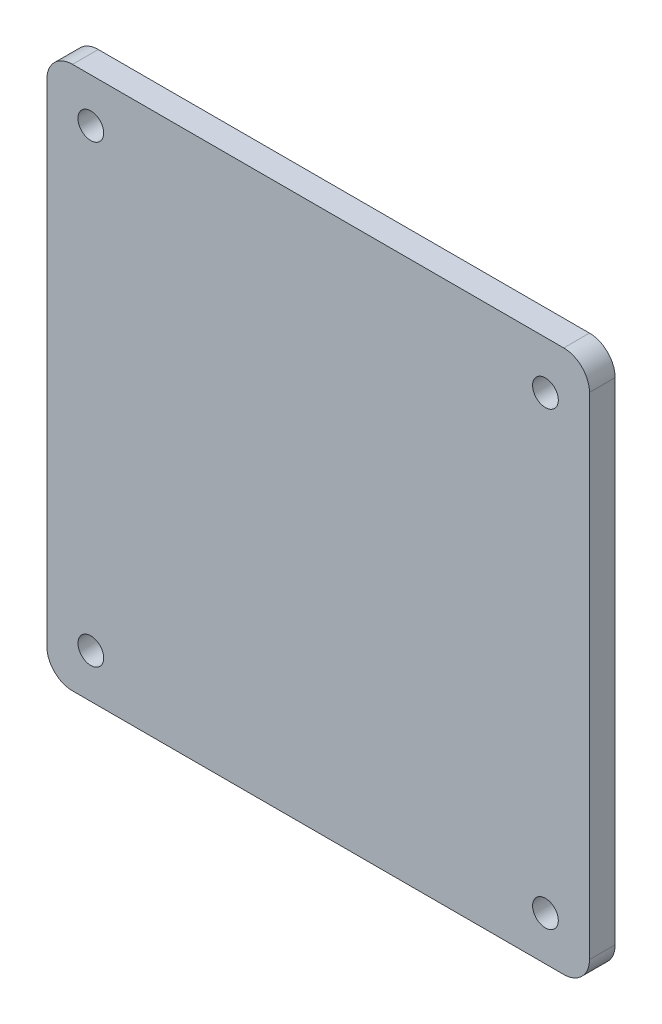
SolidWorks part; units mm, degrees
ref_plane "Front Plane" through (0, 0, 0) normal (0, 0, 1) x (1, 0, 0)
ref_plane "Top Plane" through (0, 0, 0) normal (0, 1, 0) x (1, 0, 0)
ref_plane "Right Plane" through (0, 0, 0) normal (1, 0, 0) x (0, 0, -1)
sketch "Sketch1" plane through (0, 0, 0) normal (0, 0, 1) x (1, 0, 0)
  line L1 (24.257, 26.797) -> (-24.257, 26.797)
  line L2 (26.797, 24.257) -> (26.797, -24.257)
  line L3 (24.257, -26.797) -> (-24.257, -26.797)
  line L4 (-26.797, 24.257) -> (-26.797, -24.257)
  line L5 (26.797, 26.797) -> (-26.797, -26.797) construction
  line L6 (26.797, -26.797) -> (-26.797, 26.797) construction
  arc A0 (-26.797, -24.257) -> (-24.257, -26.797) centre (-24.257, -24.257) ccw
  arc A1 (26.797, -24.257) -> (24.257, -26.797) centre (24.257, -24.257) cw
  arc A2 (24.257, 26.797) -> (26.797, 24.257) centre (24.257, 24.257) cw
  arc A3 (-26.797, 24.257) -> (-24.257, 26.797) centre (-24.257, 24.257) cw
  point P0 (0, 0)
  dimension "D3" = 2.54
  dimension "D1" = 53.594
  dimension "D2" = 53.594
extrude "Boss-Extrude1" add sketch "Sketch1" along normal blind 2.54
sketch "Sketch2" plane through (0, 0, 0) normal (0, 0, -1) x (-1, 0, 0)
  circle A0 centre (22.4506, -22.4506) radius 1.27 construction
  circle A1 centre (22.4506, -22.4506) radius 1.27
  circle A2 centre (-22.4506, -22.4506) radius 1.27 construction
  circle A3 centre (-22.4506, -22.4506) radius 1.27
  circle A4 centre (-22.4506, 22.0607) radius 1.27 construction
  circle A5 centre (-22.4506, 22.0607) radius 1.27
  circle A6 centre (22.4506, 22.4506) radius 1.27 construction
  circle A7 centre (22.4506, 22.4506) radius 1.27
extrude "Cut-Extrude1" cut sketch "Sketch2" against normal through all
